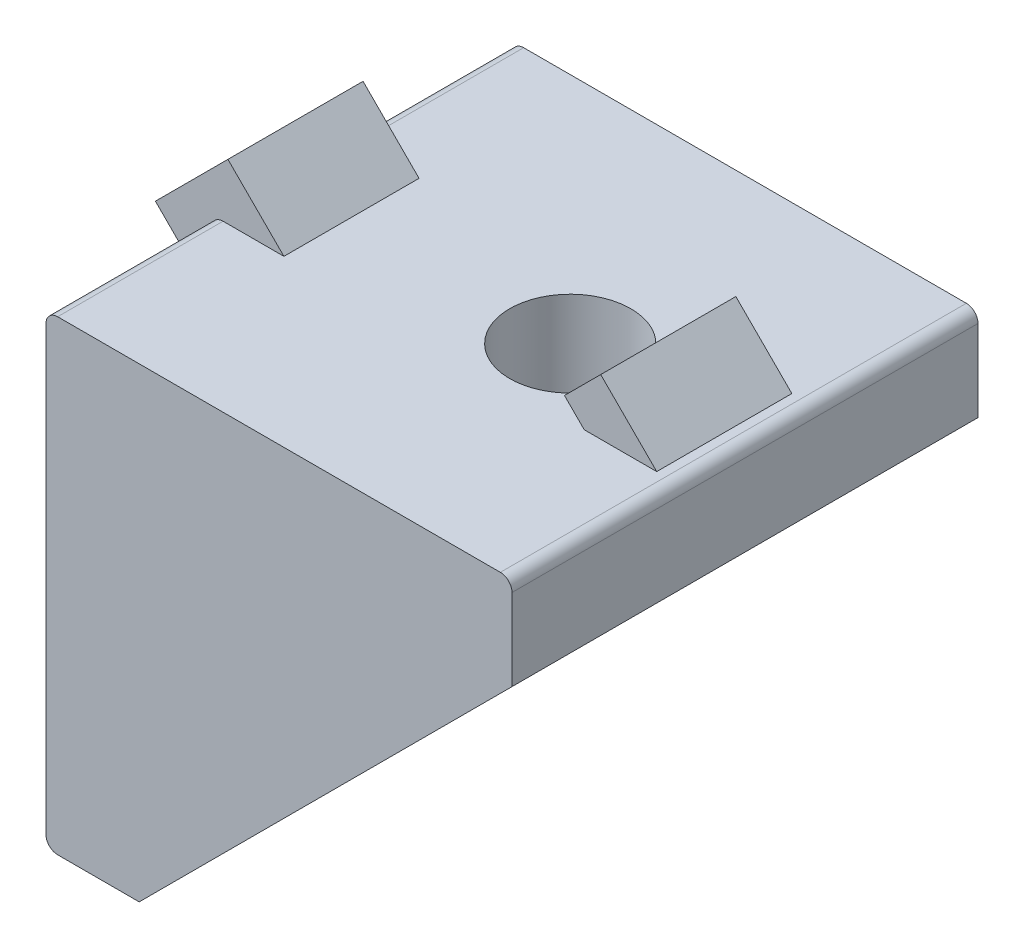
SolidWorks part; units mm, degrees
ref_plane "Спереди" through (0, 0, 0) normal (0, 0, 1) x (1, 0, 0)
ref_plane "Сверху" through (0, 0, 0) normal (0, 1, 0) x (1, 0, 0)
ref_plane "Справа" through (0, 0, 0) normal (1, 0, 0) x (0, 0, -1)
sketch "Эскиз1" plane through (0, 0, 0) normal (0, 0, 1) x (1, 0, 0)
  line L0 (0, 0) -> (0, -16)
  line L1 (0, -16) -> (-4, -16)
  line L2 (-4, -16) -> (-4, 4)
  line L3 (-4, 4) -> (16, 4)
  line L4 (16, 4) -> (16, 0)
  line L5 (16, 0) -> (0, 0)
  dimension "D1" = 20
  dimension "D2" = 20
  dimension "D3" = 4
  dimension "D4" = 4
extrude "Бобышка-Вытянуть1" add sketch "Эскиз1" along normal mid plane 20
sketch "Эскиз2" plane through (0, 0, 10) normal (0, 0, 1) x (1, 0, 0)
  line L0 (0, -16) -> (0, 0) construction
  line L1 (0, 0) -> (16, 0) construction
  line L2 (0, -16) -> (0, 0)
  line L3 (0, 0) -> (16, 0)
  line L4 (0, -16) -> (16, 0)
extrude "Бобышка-Вытянуть2" add sketch "Эскиз2" against normal blind 3
mirror "Зеркальное отражение1" about plane through (0, 0, 0) normal (0, 0, 1) of "Бобышка-Вытянуть2"
sketch "Эскиз3" plane through (0, 0, 0) normal (1, 0, 0) x (0, 0, -1)
  line L0 (-7, -16) -> (7, -16) construction
  line L1 (-10, 4) -> (-10, -16) construction
  line L2 (0, -8.5) -> (20, -8.5) construction
  line L3 (0, -8.5) -> (0, 11.5) construction
  line L4 (-7, 0) -> (7, 0) construction
  circle A0 centre (0, -8.5) radius 2.6
  circle A1 centre (20, -8.5) radius 2.6
  circle A2 centre (20, 11.5) radius 2.6
  circle A3 centre (0, 11.5) radius 2.6
  dimension "D1" = 5.2
  dimension "D3" = 10
  dimension "D4" = 2
  dimension "D9" = 5.2
  dimension "D2" = 7.5
  dimension "D6" = 90
  dimension "D7" = 20
  dimension "D8" = 20
  dimension "D5" = 2
extrude "Вырез-Вытянуть1" cut sketch "Эскиз3" against normal through all
sketch "Эскиз4" plane through (0, 0, 0) normal (0, -1, 0) x (1, 0, 0)
  line L0 (16, 7) -> (16, -7) construction
  line L1 (16, -10) -> (-4, -10) construction
  line L2 (8.5, 0) -> (-11.5, 0) construction
  line L3 (8.5, 0) -> (8.5, 20) construction
  circle A0 centre (8.5, 0) radius 2.6
  circle A1 centre (-11.5, 0) radius 2.6
  circle A2 centre (-11.5, 20) radius 2.6
  circle A3 centre (8.5, 20) radius 2.6
  dimension "D1" = 5.2
  dimension "D2" = 7.5
  dimension "D3" = 10
  dimension "D6" = 90
  dimension "D7" = 20
  dimension "D8" = 20
  dimension "D4" = 2
  dimension "D5" = 2
extrude "Вырез-Вытянуть2" cut sketch "Эскиз4" against normal through all
sketch "Эскиз5" plane through (0, 0, 10) normal (0, 0, 1) x (1, 0, 0)
  line L0 (-0.8887, 4) -> (-3.2929, 6.4042)
  line L1 (16, 4) -> (-4, 4) construction
  line L2 (-3.2929, 6.4042) -> (-6.4042, 3.2929)
  line L3 (-6.4042, 3.2929) -> (-4, 0.8887)
  line L4 (-4, 4) -> (-4, -16) construction
  line L5 (-4, 0.8887) -> (-4, 4)
  line L6 (-4, 4) -> (-0.8887, 4)
  line L7 (16, 3.1113) -> (12.7071, 6.4042)
  line L8 (12.7071, 6.4042) -> (11.1515, 4.8485)
  line L9 (11.1515, 4.8485) -> (16, 0)
  line L10 (0, -16) -> (16, 0) construction
  line L12 (12.7071, 6.4042) -> (-3.2929, 6.4042) construction
  line L13 (16, 0) -> (16, 4) construction
  line L14 (16, 0) -> (16, 3.1113)
  line L15 (-1.2692, 1.2692) -> (35354.0698, -35354.0698) construction
  line L16 (-4.8485, -11.1515) -> (0, -16)
  line L17 (-6.4042, -12.7071) -> (-4.8485, -11.1515)
  line L18 (-3.1113, -16) -> (-6.4042, -12.7071)
  line L19 (0, -16) -> (-3.1113, -16)
  point P8 (12, 4)
  dimension "D1" = 45
  dimension "D2" = 4.4
  dimension "D3" = 2.2
  dimension "D4" = 1.2
  dimension "D5" = 2.2
  dimension "D6" = 1.2
  dimension "D7" = 2.4042
  dimension "D8" = 45
extrude "Бобышка-Вытянуть3" add sketch "Эскиз5" along normal mid plane 5.8 from offset 10 offset against normal yes
fillet "Скругление1" radius 0.5 4 edges at (-4, 4, -6.45) (-4, 4, 6.45) (-4, -16, 0) (16, 4, 0)
chamfer "Фаска1" distance 1 angle 45 5 edges at (0, -8, -7) (0, -8, 7) (8, 0, 7) (0, 0, 0) (8, 0, -7)
